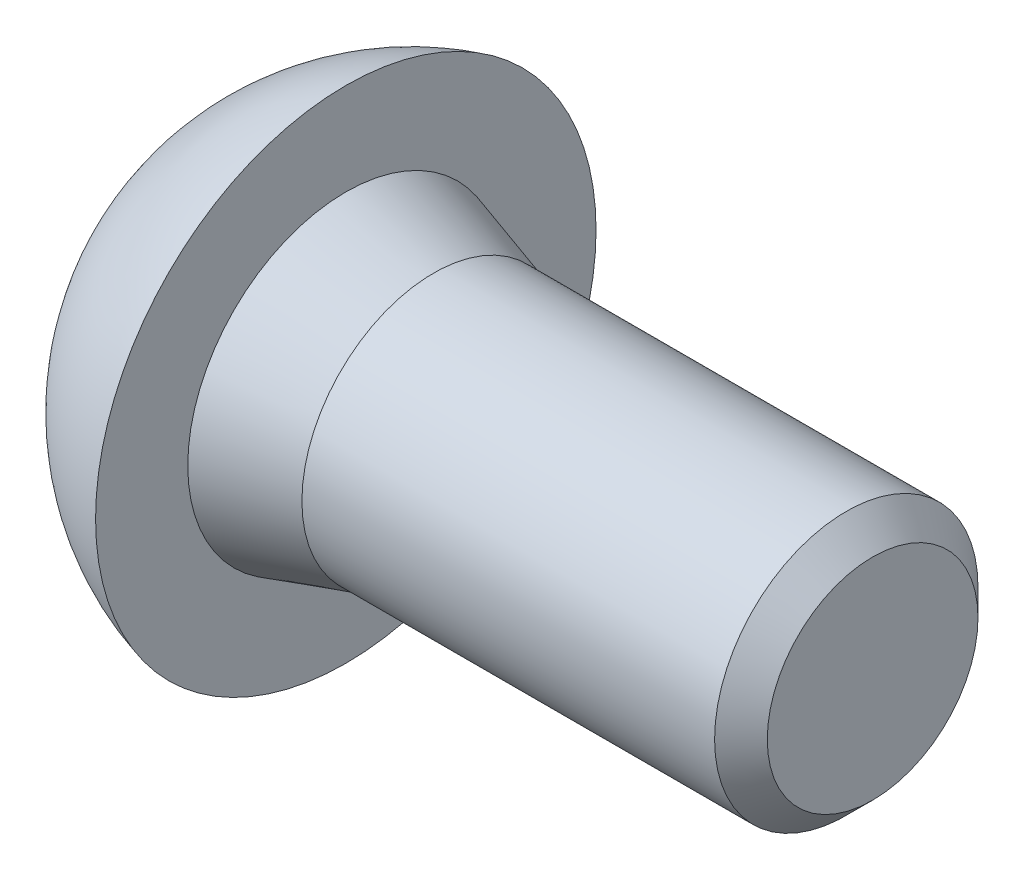
SolidWorks part; units mm, degrees
ref_plane "前视基准面" through (0, 0, 0) normal (0, 0, 1) x (1, 0, 0)
ref_plane "上视基准面" through (0, 0, 0) normal (0, 1, 0) x (1, 0, 0)
ref_plane "右视基准面" through (0, 0, 0) normal (1, 0, 0) x (0, 0, -1)
sketch "草图1" plane through (0, 0, 0) normal (0, 0, 1) x (1, 0, 0)
  line L0 (0, 0) -> (0, 1.5)
  line L1 (0, 1.5) -> (-5, 1.5)
  line L2 (-5, 1.5) -> (-6, 1.8)
  line L3 (-6, 1.8) -> (-6, 2.85)
  line L4 (0, 0) -> (-7.65, 0)
  line L5 (0, 0) -> (-159.9915, 0) construction
  line L6 (-7.65, 1.71) -> (-7.65, 0)
  arc A0 (-6, 2.85) -> (-7.65, 1.71) centre (-5.2497, 0) ccw
  dimension "D2" = 6
  dimension "D1" = 3
  dimension "D3" = 3.6
  dimension "D4" = 5.7
  dimension "D5" = 1
  dimension "D6" = 3.42
  dimension "D7" = 1.65
revolve "旋转1" add sketch "草图1" angle 360 about L5
sketch "草图4" plane through (-7.65, 0, 0) normal (-1, 0, 0) x (0, 0, 1)
  line L1 (0, 1.1547) -> (-1, 0.5774)
  line L2 (-1, 0.5774) -> (-1, -0.5774)
  line L3 (-1, -0.5774) -> (0, -1.1547)
  line L4 (0, -1.1547) -> (1, -0.5774)
  line L5 (1, -0.5774) -> (1, 0.5774)
  line L6 (1, 0.5774) -> (0, 1.1547)
  circle A0 centre (0, 0) radius 1 construction
  dimension "D1" = 2
extrude "切除-拉伸1" cut sketch "草图4" against normal blind 1.04
chamfer "倒角1" distance 0.3 angle 45 1 edges at (0, 0, -1.5)
ref_plane "基准面2" through (-6.4038, 0, 0) normal (-1, 0, 0) x (0, 0, 1)
sketch "草图6" plane through (-6.61, 0, 0) normal (-1, 0, 0) x (0, 0, 1)
  line L1 (0, 1.1547) -> (-1, 0.5774)
  line L2 (-1, 0.5774) -> (-1, -0.5774)
  line L3 (-1, -0.5774) -> (0, -1.1547)
  line L4 (0, -1.1547) -> (1, -0.5774)
  line L5 (1, -0.5774) -> (1, 0.5774)
  line L6 (1, 0.5774) -> (0, 1.1547)
  circle A0 centre (0, 0) radius 1 construction
sketch "草图7" plane through (-6.4038, 0, 0) normal (-1, 0, 0) x (0, 0, 1)
  point P0 (0, 0)
loft "切除-放样1" cut profiles "草图7", "草图6"
